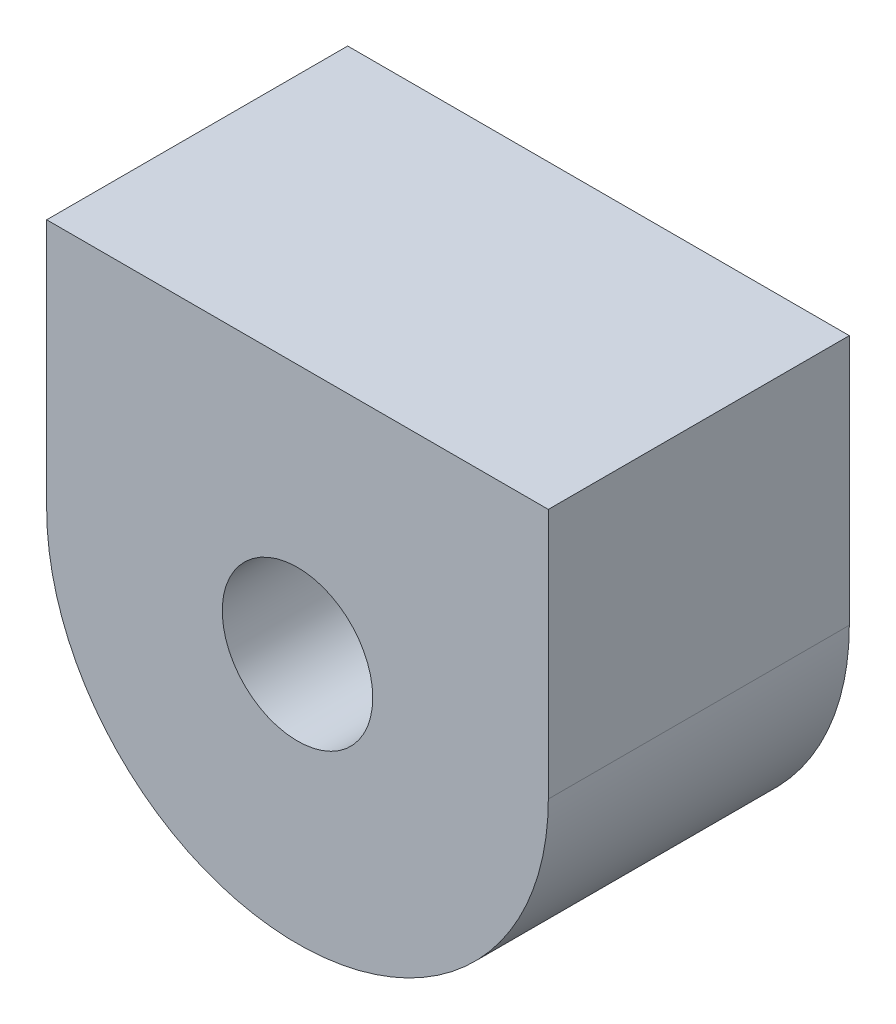
SolidWorks part; units mm, degrees
ref_plane "Front Plane" through (0, 0, 0) normal (0, 0, 1) x (1, 0, 0)
ref_plane "Top Plane" through (0, 0, 0) normal (0, 1, 0) x (1, 0, 0)
ref_plane "Right Plane" through (0, 0, 0) normal (1, 0, 0) x (0, 0, -1)
sketch "Sketch1" plane through (0, 0, 0) normal (0, 0, 1) x (1, 0, 0)
  line L0 (0, 0) -> (0, 5)
  line L1 (0, 5) -> (10, 5)
  line L2 (10, 5) -> (10, 0)
  arc A0 (0, 0) -> (10, 0) centre (5, 0) ccw
  circle A1 centre (5, 0) radius 1.5
  point P7 (0, 0)
  dimension "D2" = 3
  dimension "D1" = 10
  dimension "D3" = 5
extrude "Boss-Extrude1" add sketch "Sketch1" along normal blind 6
